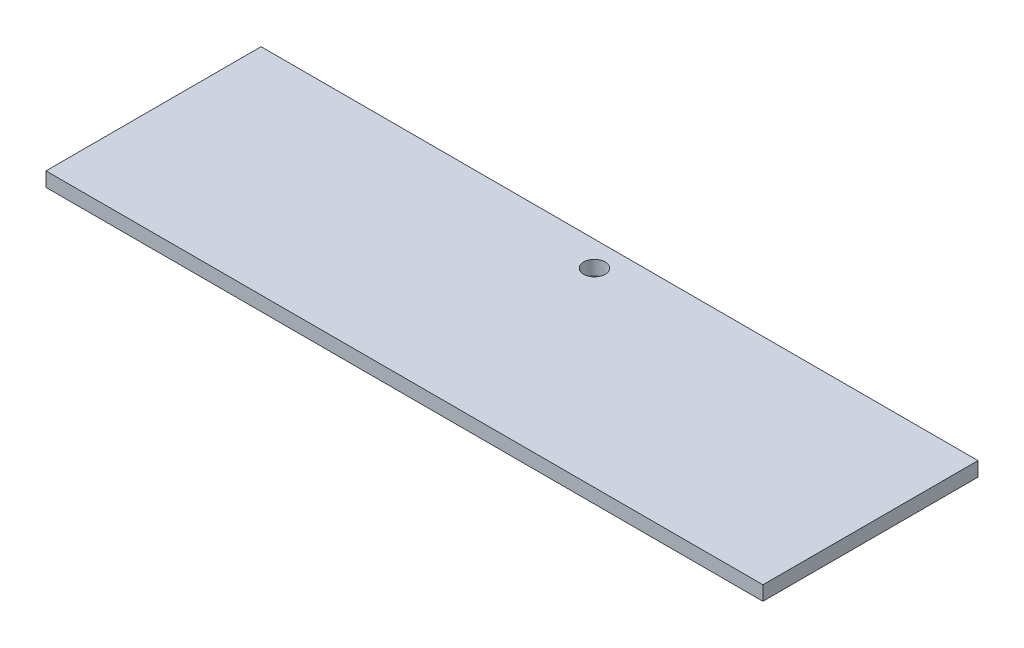
SolidWorks part; units mm, degrees
ref_plane "Front Plane" through (0, 0, 0) normal (0, 0, 1) x (1, 0, 0)
ref_plane "Top Plane" through (0, 0, 0) normal (0, 1, 0) x (1, 0, 0)
ref_plane "Right Plane" through (0, 0, 0) normal (1, 0, 0) x (0, 0, -1)
sketch "Sketch1" plane through (0, 0, 0) normal (0, 1, 0) x (1, 0, 0)
  line L1 (-317.5, -95.25) -> (317.5, -95.25)
  line L2 (-317.5, -95.25) -> (-317.5, 95.25)
  line L3 (-317.5, 95.25) -> (317.5, 95.25)
  line L4 (317.5, -95.25) -> (317.5, 95.25)
  line L5 (-317.5, -95.25) -> (317.5, 95.25) construction
  line L6 (-317.5, 95.25) -> (317.5, -95.25) construction
  point P0 (0, 0)
  dimension "D1" = 190.5
  dimension "D2" = 635
extrude "Boss-Extrude1" add sketch "Sketch1" against normal blind 12.7
sketch "Sketch2" plane through (0, 0, 0) normal (0, 1, 0) x (1, 0, 0)
  line L0 (0, 95.25) -> (0, 82.55) construction
  line L1 (317.5, 95.25) -> (-317.5, 95.25) construction
  circle A0 centre (0, 73.025) radius 9.525
  dimension "D2" = 19.05
  dimension "D1" = 12.7
extrude "Cut-Extrude1" cut sketch "Sketch2" against normal through all
